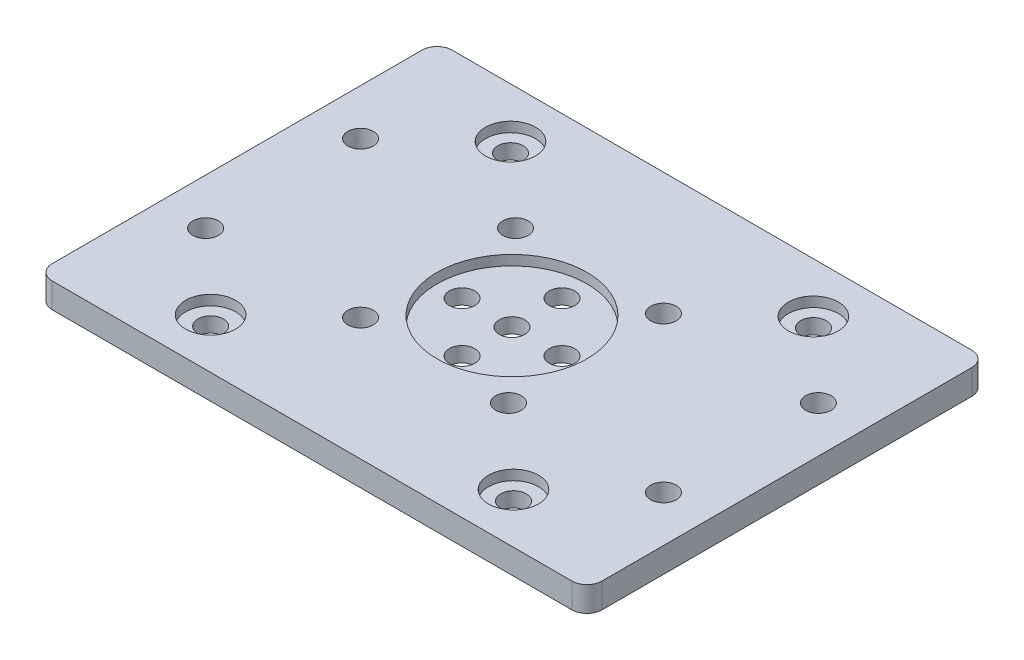
SolidWorks part; units mm, degrees
material "6061-T6 (SS)"
ref_plane "Front Plane" through (0, 0, 0) normal (0, 0, 1) x (1, 0, 0)
ref_plane "Top Plane" through (0, 0, 0) normal (0, 1, 0) x (1, 0, 0)
ref_plane "Right Plane" through (0, 0, 0) normal (1, 0, 0) x (0, 0, -1)
sketch "Sketch1" plane through (0, 0, 0) normal (0, 1, 0) x (1, 0, 0)
  line L0 (0, 0) -> (55, 0) construction
  line L1 (52, -40) -> (-52, -40)
  line L2 (55, -37) -> (55, 37)
  line L3 (52, 40) -> (-52, 40)
  line L4 (-55, -37) -> (-55, 37)
  line L5 (0, 40) -> (0, 0) construction
  arc A0 (-52, -40) -> (-55, -37) centre (-52, -37) cw
  arc A1 (52, -40) -> (55, -37) centre (52, -37) ccw
  arc A2 (55, 37) -> (52, 40) centre (52, 37) ccw
  arc A3 (-52, 40) -> (-55, 37) centre (-52, 37) ccw
  circle A4 centre (-30.3, 30) radius 2.55
  circle A5 centre (0, 10) radius 2.55
  circle A6 centre (0, 0) radius 2.55
  circle A7 centre (10, 0) radius 2.55
  circle A8 centre (-10, 0) radius 2.55
  circle A16 centre (-45.8, 15.5) radius 2.55
  circle A23 centre (30.3, 30) radius 2.55
  circle A30 centre (0, -10) radius 2.55
  circle A33 centre (-14.8, 15.5) radius 2.55
  circle A43 centre (14.8, 15.5) radius 2.55
  circle A46 centre (45.8, 15.5) radius 2.55
  circle A53 centre (30.3, -30) radius 2.55
  circle A54 centre (45.8, -15.5) radius 2.55
  circle A57 centre (14.8, -15.5) radius 2.55
  circle A60 centre (-14.8, -15.5) radius 2.55
  circle A63 centre (-45.8, -15.5) radius 2.55
  circle A66 centre (-30.3, -30) radius 2.55
  point P0 (0, 0)
  dimension "D2" = 3
  dimension "D3" = 5.1
  dimension "D5" = 60
  dimension "D10" = 10
  dimension "D1" = 80
  dimension "D4" = 10
  dimension "D6" = 15.5
  dimension "D8" = 31
  dimension "D9" = 110
  dimension "D11" = 60
  dimension "D12" = 30.3
  dimension "D13" = 30.3
extrude "Boss-Extrude1" add sketch "Sketch1" along normal blind 5
sketch "草圖1" plane through (0, 5, 0) normal (0, 1, 0) x (1, 0, 0)
  circle A0 centre (-30.3, -30) radius 5
  circle A1 centre (-30.3, 30) radius 5
  circle A2 centre (30.3, -30) radius 5
  circle A3 centre (30.3, 30) radius 5
  circle A4 centre (0, 0) radius 15
extrude "除料-伸長1" cut sketch "草圖1" against normal blind 2
